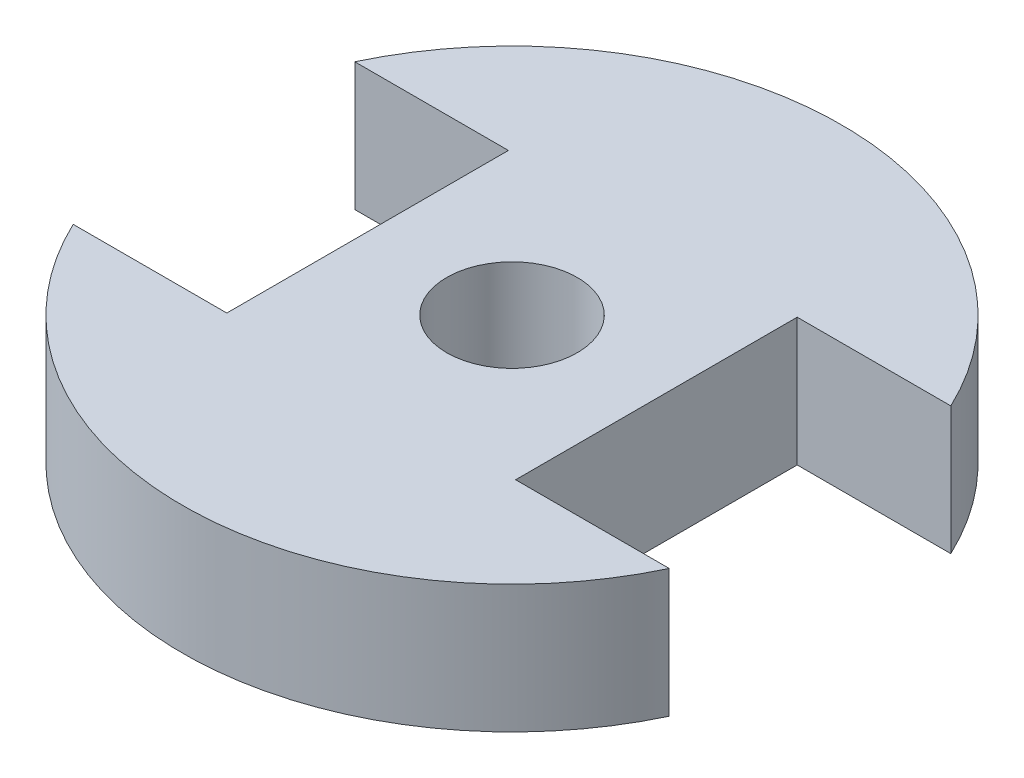
SolidWorks part; units mm, degrees
ref_plane "Front Plane" through (0, 0, 0) normal (0, 0, 1) x (1, 0, 0)
ref_plane "Top Plane" through (0, 0, 0) normal (0, 1, 0) x (1, 0, 0)
ref_plane "Right Plane" through (0, 0, 0) normal (1, 0, 0) x (0, 0, -1)
sketch "Sketch1" plane through (0, 0, 0) normal (0, 1, 0) x (1, 0, 0)
  line L0 (-11.6411, 5.5) -> (-5.6411, 5.5)
  line L1 (-5.6411, 5.5) -> (-5.6411, -5.5)
  line L2 (-5.6411, -5.5) -> (-11.6411, -5.5)
  line L3 (0, 0) -> (-5.6411, 0) construction
  line L4 (11.6411, 5.5) -> (5.6411, 5.5)
  line L5 (5.6411, 5.5) -> (5.6411, -5.5)
  line L6 (5.6411, -5.5) -> (11.6411, -5.5)
  line L7 (0, 12.875) -> (0, -12.875) construction
  line L8 (5.6411, 0) -> (0, 0) construction
  circle A0 centre (0, 0) radius 15.875 construction
  arc A1 (-11.6411, -5.5) -> (11.6411, -5.5) centre (0, 0) ccw
  circle A2 centre (0, 0) radius 2.55
  arc A3 (11.6411, 5.5) -> (-11.6411, 5.5) centre (0, 0) ccw
  arc A4 (-11.6411, 5.5) -> (-11.6411, -5.5) centre (0, 0) ccw construction
  arc A5 (11.6411, -5.5) -> (11.6411, 5.5) centre (0, 0) ccw construction
  dimension "D1" = 31.75
  dimension "D2" = 3
  dimension "D4" = 5.1
  dimension "D6" = 12.875
  dimension "D3" = 6
  dimension "D5" = 11
  dimension "D7" = 25.75
extrude "Boss-Extrude1" add sketch "Sketch1" along normal blind 5
